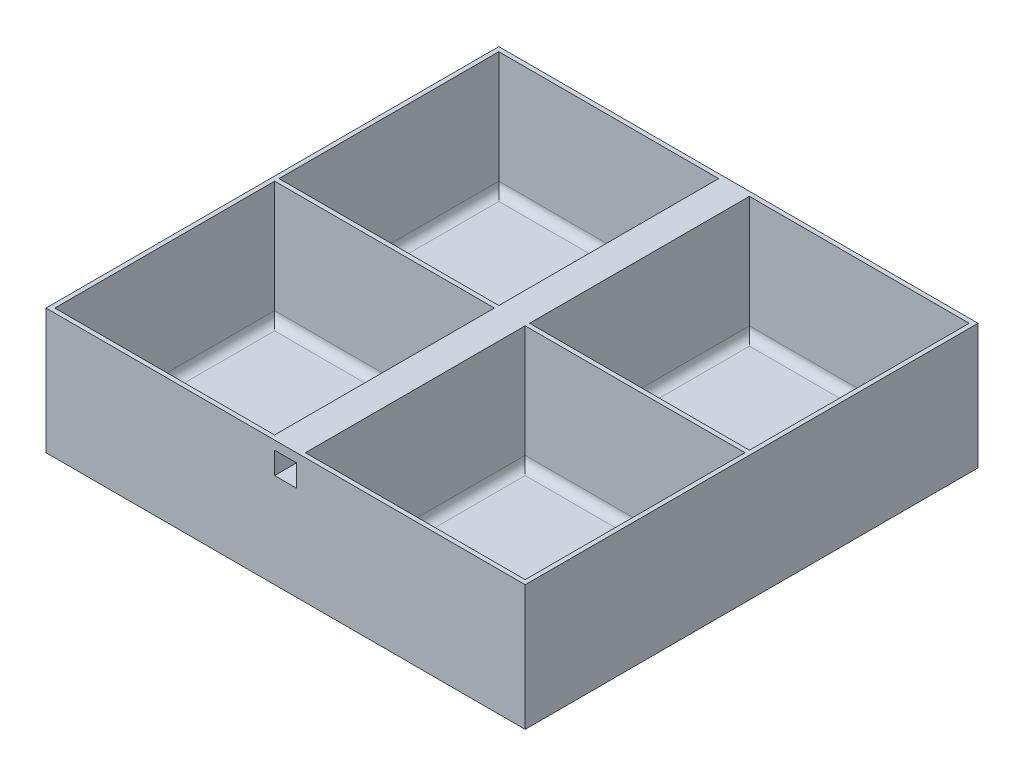
SolidWorks part; units mm, degrees
material "PVAL"
ref_plane "Front Plane" through (0, 0, 0) normal (0, 0, 1) x (1, 0, 0)
ref_plane "Top Plane" through (0, 0, 0) normal (0, 1, 0) x (1, 0, 0)
ref_plane "Right Plane" through (0, 0, 0) normal (1, 0, 0) x (0, 0, -1)
sketch "Sketch1" plane through (0, 0, 0) normal (0, 1, 0) x (1, 0, 0)
  line L1 (109, 103) -> (-109, 103)
  line L2 (109, 103) -> (109, -103)
  line L3 (109, -103) -> (-109, -103)
  line L4 (-109, 103) -> (-109, -103)
  line L5 (109, 103) -> (-109, -103) construction
  line L6 (109, -103) -> (-109, 103) construction
  line L7 (-107, -1) -> (-7, -1)
  line L8 (-107, -1) -> (-107, -101)
  line L9 (-107, -101) -> (-7, -101)
  line L10 (-7, -1) -> (-7, -101)
  line L11 (7, -1) -> (107, -1)
  line L12 (7, -1) -> (7, -101)
  line L13 (7, -101) -> (107, -101)
  line L14 (107, -1) -> (107, -101)
  line L15 (-7, 101) -> (-107, 101)
  line L16 (-7, 101) -> (-7, 1)
  line L17 (-7, 1) -> (-107, 1)
  line L18 (-107, 101) -> (-107, 1)
  line L19 (107, 101) -> (7, 101)
  line L20 (107, 101) -> (107, 1)
  line L21 (107, 1) -> (7, 1)
  line L22 (7, 101) -> (7, 1)
  point P1 (0, 0)
  dimension "D1" = 218
  dimension "D2" = 206
  dimension "D3" = 100
  dimension "D4" = 100
  dimension "D5" = 2
  dimension "D6" = 2
  dimension "D7" = 2
  dimension "D8" = 2
extrude "Boss-Extrude1" add sketch "Sketch1" along normal blind 57
sketch "Sketch2" plane through (0, 0, 0) normal (0, 1, 0) x (1, 0, 0)
  line L0 (-109, 103) -> (-109, -103) construction
  line L1 (109, 103) -> (-109, 103) construction
  line L3 (-109, -103) -> (109, -103) construction
  line L4 (109, -103) -> (109, 103) construction
  line L5 (-109, -103) -> (109, -103)
  line L6 (109, -103) -> (109, 103)
  line L7 (109, 103) -> (-109, 103)
  line L8 (-109, 103) -> (-109, -103)
extrude "Boss-Extrude2" add sketch "Sketch2" along normal blind 2
fillet "Fillet1" radius 4 16 edges at (107, 2, -51) (57, 2, -101) (7, 2, -51) (57, 2, -1) (-57, 2, -101) (-107, 2, -51) (-7, 2, -51) (-57, 2, -1) (-107, 2, 51) (-57, 2, 1) (-7, 2, 51) (-57, 2, 101) (107, 2, 51) (57, 2, 101) (7, 2, 51) (57, 2, 1)
sketch "Sketch3" plane through (0, 0, -103) normal (0, 0, -1) x (-1, 0, 0)
  line L0 (0, 57) -> (0, 53) construction
  line L1 (5, 53) -> (-5, 53)
  line L2 (5, 53) -> (5, 43)
  line L3 (5, 43) -> (-5, 43)
  line L4 (-5, 53) -> (-5, 43)
  line L5 (5, 53) -> (-5, 43) construction
  line L6 (5, 43) -> (-5, 53) construction
  line L7 (-109, 57) -> (109, 57) construction
  point P0 (0, 48)
  point P5 (0, 0)
  dimension "D1" = 10
  dimension "D2" = 10
  dimension "D3" = 4
extrude "Cut-Extrude1" cut sketch "Sketch3" against normal through all
equation "\"t\"= 2'Wall thickness"
equation "\"tank_l\"= 100'tank partition length"
equation "\"tank_w\"= 100'tank partition width"
equation "\"tank_h\"= 55'tank partition height"
equation "\"spar_w\" = 10'spar width"
equation "\"spar_h\"= 10'spar height"
equation "\"D1@Sketch1\"=(\"tank_l\"*2) + (\"t\"*4) + (\"spar_w\")"
equation "\"D2@Sketch1\"=(\"tank_w\"*2)+(\"t\"*3)"
equation "\"D3@Sketch1\"= \"tank_w\""
equation "\"D4@Sketch1\"=\"tank_l\""
equation "\"D5@Sketch1\"=\"t\""
equation "\"D6@Sketch1\"=\"t\""
equation "\"D7@Sketch1\"=\"t\""
equation "\"D8@Sketch1\"=\"t\""
equation "\"D1@Boss-Extrude2\"=\"t\""
equation "\"D1@Boss-Extrude1\"=\"tank_h\"+\"t\""
equation "\"D1@Sketch3\"=\"spar_w\""
equation "\"D2@Sketch3\"=\"spar_h\""
